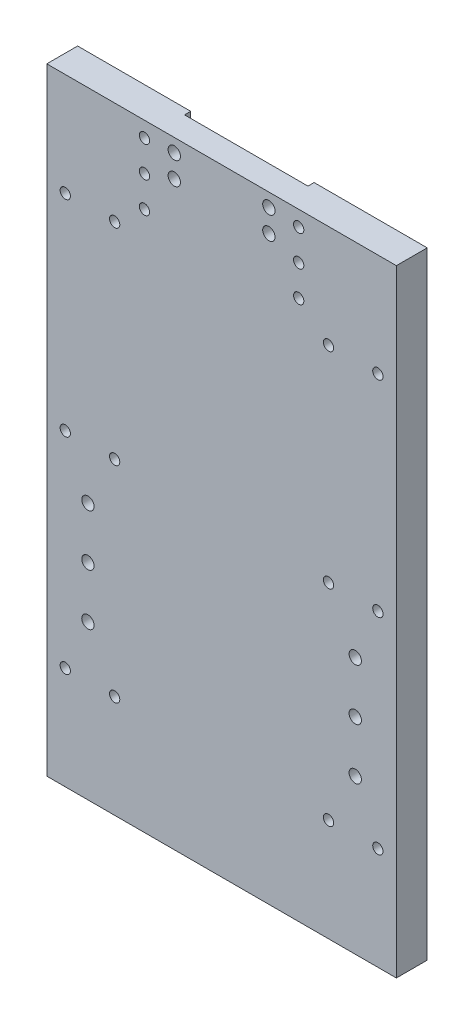
SolidWorks part; units mm, degrees
ref_plane "Plan de face" through (0, 0, 0) normal (0, 0, 1) x (1, 0, 0)
ref_plane "Plan de dessus" through (0, 0, 0) normal (0, 1, 0) x (1, 0, 0)
ref_plane "Plan de droite" through (0, 0, 0) normal (1, 0, 0) x (0, 0, -1)
sketch "Esquisse1" plane through (0, 0, 0) normal (0, 0, 1) x (1, 0, 0)
  line L1 (0, 0) -> (170, 0)
  line L2 (0, 0) -> (0, 300)
  line L3 (0, 300) -> (170, 300)
  line L4 (170, 0) -> (170, 300)
  dimension "D1" = 170
  dimension "D2" = 300
extrude "Boss.-Extru.1" add sketch "Esquisse1" along normal blind 15
sketch "Esquisse2" plane through (0, 0, 15) normal (0, 0, 1) x (1, 0, 0)
  line L0 (85, 0) -> (85, 300) construction
  line L1 (0, 0) -> (170, 0) construction
  line L2 (170, 300) -> (0, 300) construction
  line L3 (21, 300) -> (21, 0) construction
  line L4 (85, 150) -> (0, 150) construction
  line L5 (0, 300) -> (0, 0) construction
  line L6 (9, 150) -> (9, 250) construction
  line L7 (161, 150) -> (161, 250) construction
  circle A0 centre (9, 250) radius 2.5
  circle A1 centre (33, 250) radius 2.5
  circle A2 centre (9, 150) radius 2.5
  circle A3 centre (33, 150) radius 2.5
  circle A4 centre (33, 50) radius 2.5
  circle A5 centre (9, 50) radius 2.5
  circle A6 centre (161, 50) radius 2.5
  circle A7 centre (137, 50) radius 2.5
  circle A8 centre (137, 150) radius 2.5
  circle A9 centre (161, 150) radius 2.5
  circle A10 centre (137, 250) radius 2.5
  circle A11 centre (161, 250) radius 2.5
  dimension "D3" = 5
  dimension "D1" = 64
  dimension "D2" = 24
  dimension "D4" = 100
extrude "Enlèv. mat.-Extru.1" cut sketch "Esquisse2" against normal up to vertex (15 mm away) up to point (170, 300, 0)
sketch "Esquisse3" plane through (0, 0, 0) normal (0, 0, -1) x (-1, 0, 0)
  line L0 (-170, 300) -> (0, 300) construction
  line L1 (-115, 300) -> (-55, 300)
  line L2 (-115, 300) -> (-115, 275)
  line L3 (-115, 275) -> (-55, 275)
  line L4 (-55, 300) -> (-55, 275)
  line L5 (-85, 275) -> (-85, 300) construction
  dimension "D1" = 60
  dimension "D2" = 25
extrude "Enlèv. mat.-Extru.2" cut sketch "Esquisse3" against normal blind 3
sketch "Esquisse4" plane through (0, 0, 3) normal (0, 0, -1) x (-1, 0, 0)
  line L0 (-108, 282.5) -> (-62, 282.5) construction
  line L1 (-62, 282.5) -> (-62, 293.5) construction
  line L2 (-62, 293.5) -> (-108, 293.5) construction
  line L3 (-108, 293.5) -> (-108, 282.5) construction
  line L4 (-85, 300) -> (-85, 293.5) construction
  line L5 (-55, 300) -> (-115, 300) construction
  circle A0 centre (-108, 293.5) radius 3
  circle A1 centre (-62, 293.5) radius 3
  circle A2 centre (-108, 282.5) radius 3
  circle A3 centre (-62, 282.5) radius 3
  dimension "D3" = 6
  dimension "D1" = 46
  dimension "D2" = 11
  dimension "D4" = 6.5
extrude "Enlèv. mat.-Extru.3" cut sketch "Esquisse4" against normal up to vertex (12 mm away)
sketch "Esquisse5" plane through (0, 0, 15) normal (0, 0, 1) x (1, 0, 0)
  line L0 (85, 300) -> (85, 248.2976) construction
  line L1 (170, 300) -> (0, 300) construction
  line L2 (47.5, 292.5) -> (47.5, 277.5) construction
  line L3 (47.5, 277.5) -> (66.2336, 277.5) construction
  line L4 (122.5, 292.5) -> (122.5, 277.5) construction
  circle A0 centre (47.5, 292.5) radius 2.5
  circle A1 centre (47.5, 277.5) radius 2.5
  circle A2 centre (47.5, 262.5) radius 2.5
  circle A3 centre (122.5, 262.5) radius 2.5
  circle A4 centre (122.5, 277.5) radius 2.5
  circle A5 centre (122.5, 292.5) radius 2.5
  dimension "D2" = 5
  dimension "D1" = 15
  dimension "D3" = 75
  dimension "D4" = 22.5
extrude "Enlèv. mat.-Extru.4" cut sketch "Esquisse5" against normal up to vertex
sketch "Esquisse6" plane through (0, 0, 15) normal (0, 0, 1) x (1, 0, 0)
  line L0 (85, 0) -> (85, 300) construction
  line L1 (0, 0) -> (170, 0) construction
  line L2 (170, 300) -> (0, 300) construction
  line L3 (0, 100) -> (170, 100) construction
  line L4 (0, 300) -> (0, 0) construction
  line L5 (170, 0) -> (170, 300) construction
  line L6 (20, 100) -> (20, 125) construction
  line L7 (150, 100) -> (150, 125) construction
  circle A0 centre (20, 100) radius 3
  circle A1 centre (20, 125) radius 3
  circle A2 centre (20, 75) radius 3
  circle A3 centre (150, 75) radius 3
  circle A4 centre (150, 125) radius 3
  circle A5 centre (150, 100) radius 3
  dimension "D1" = 6
  dimension "D2" = 130
  dimension "D3" = 100
  dimension "D4" = 25
extrude "Enlèv. mat.-Extru.5" cut sketch "Esquisse6" against normal up to vertex (15 mm away) up to point (170, 0, 0)
